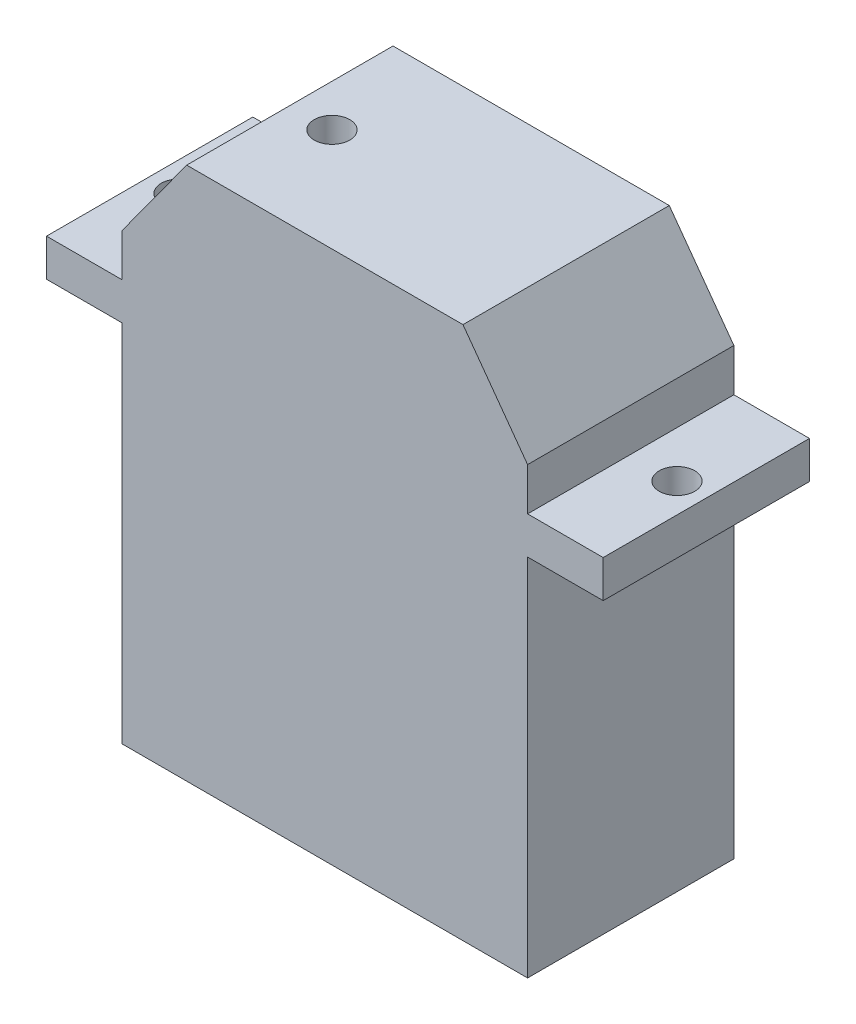
SolidWorks part; units mm, degrees
ref_plane "Front Plane" through (0, 0, 0) normal (0, 0, 1) x (1, 0, 0)
ref_plane "Top Plane" through (0, 0, 0) normal (0, 1, 0) x (1, 0, 0)
ref_plane "Right Plane" through (0, 0, 0) normal (1, 0, 0) x (0, 0, -1)
sketch "Sketch1" plane through (0, 0, 0) normal (0, 0, 1) x (1, 0, 0)
  line L1 (11.4, 15) -> (-11.4, 15)
  line L2 (11.4, 15) -> (11.4, -15)
  line L3 (11.4, -15) -> (-11.4, -15)
  line L4 (-11.4, 15) -> (-11.4, -15)
  line L5 (11.4, 15) -> (-11.4, -15) construction
  line L6 (11.4, -15) -> (-11.4, 15) construction
  point P0 (0, 0)
  dimension "D1" = 22.8
  dimension "D2" = 30
extrude "Boss-Extrude1" add sketch "Sketch1" along normal blind 11.6
sketch "Sketch2" plane through (0, 15, 0) normal (0, 1, 0) x (1, 0, 0)
  line L0 (-11.4, -5.8) -> (11.4, -5.8) construction
  line L1 (-11.4, -11.6) -> (-11.4, 0) construction
  line L2 (11.4, -11.6) -> (11.4, 0) construction
  circle A0 centre (-5.4, -5.8) radius 1
  dimension "D1" = 6
sketch "Sketch3" plane through (0, 0, 11.6) normal (0, 0, 1) x (1, 0, 0)
  line L0 (0, 15) -> (0, -15) construction
  line L1 (-11.4, 15) -> (11.4, 15) construction
  line L2 (-11.4, -15) -> (11.4, -15) construction
  line L3 (-11.4, 15) -> (-11.4, -15) construction
  line L4 (-11.4, 7.6) -> (-15.65, 7.6)
  line L5 (-11.4, 7.6) -> (-11.4, 5.5)
  line L6 (-11.4, 5.5) -> (-15.65, 5.5)
  line L7 (-15.65, 7.6) -> (-15.65, 5.5)
  line L8 (11.4, 5.5) -> (15.65, 5.5)
  line L9 (15.65, 7.6) -> (15.65, 5.5)
  line L10 (11.4, 7.6) -> (15.65, 7.6)
  line L11 (11.4, 7.6) -> (11.4, 5.5)
  dimension "D1" = 15.65
  dimension "D2" = 2.1
  dimension "D3" = 20.5
extrude "Boss-Extrude2" add sketch "Sketch3" against normal up to surface (11.6 mm away) up to face at (0, 0, 0)
sketch "Sketch4" plane through (0, 7.6, 0) normal (0, 1, 0) x (1, 0, 0)
  line L0 (-15.65, -5.8) -> (-11.4, -5.8) construction
  line L1 (-15.65, 0) -> (-15.65, -11.6) construction
  line L2 (-11.4, 0) -> (-11.4, -11.6) construction
  line L3 (0, -12.0259) -> (0, 3.5396) construction
  circle A0 centre (-14, -5.8) radius 1
  circle A1 centre (14, -5.8) radius 1
  point P13 (0, 0)
  dimension "D1" = 14
extrude "Cut-Extrude1" cut sketch "Sketch4" against normal blind 11.6
extrude "Cut-Extrude2" cut sketch "Sketch2" against normal blind 5
chamfer "Chamfer1" distance 5 angle 36 2 edges at (-11.4, 15, 5.8) (11.4, 15, 5.8)
